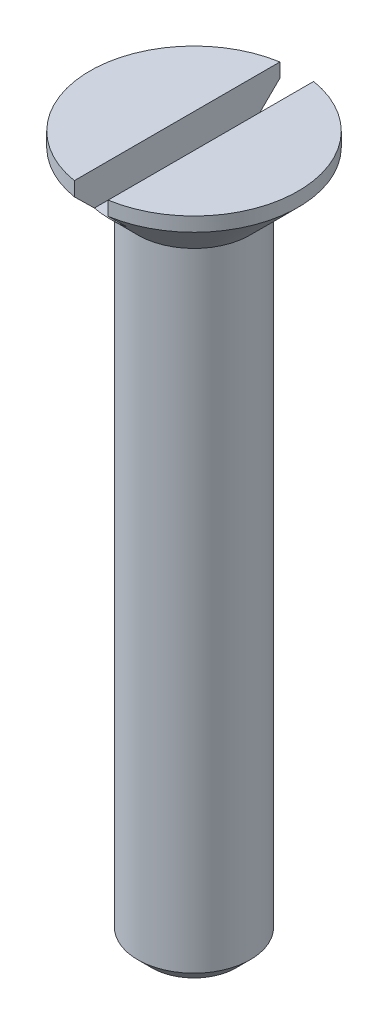
SolidWorks part; units mm, degrees
ref_plane "Спереди" through (0, 0, 0) normal (0, 0, 1) x (1, 0, 0)
ref_plane "Сверху" through (0, 0, 0) normal (0, 1, 0) x (1, 0, 0)
ref_plane "Справа" through (0, 0, 0) normal (1, 0, 0) x (0, 0, -1)
sketch "Эскиз1" plane through (0, 0, 0) normal (0, 0, 1) x (1, 0, 0)
  line L0 (0, 0) -> (-1.5, 0)
  line L1 (-1.5, 0) -> (-2, 0.5)
  line L2 (-2, 0.5) -> (-2, 22.8)
  line L3 (-2, 22.8) -> (-3.7, 24.5)
  line L4 (-3.7, 24.5) -> (-3.7, 25)
  line L5 (-3.7, 25) -> (0, 25)
  line L6 (0, 25) -> (0, 0)
  dimension "D1" = 2
  dimension "D2" = 45
  dimension "D3" = 1.5
  dimension "D4" = 25
  dimension "D5" = 45
  dimension "D6" = 2.2
  dimension "D7" = 3.7
revolve "Повернуть1" add sketch "Эскиз1" angle 360 about L6
sketch "Эскиз2" plane through (0, 0, 0) normal (0, 0, 1) x (1, 0, 0)
  line L0 (0, 0) -> (0, 25) construction
  line L1 (3.7, 25) -> (-3.7, 25) construction
  line L3 (-0.6, 25) -> (0.6, 25)
  line L4 (-0.6, 25) -> (-0.6, 23.8)
  line L5 (-0.6, 23.8) -> (0.6, 23.8)
  line L6 (0.6, 25) -> (0.6, 23.8)
  dimension "D1" = 1.2
  dimension "D2" = 1.2
extrude "Вырез-Вытянуть1" cut sketch "Эскиз2" against normal through all and the other way through all
